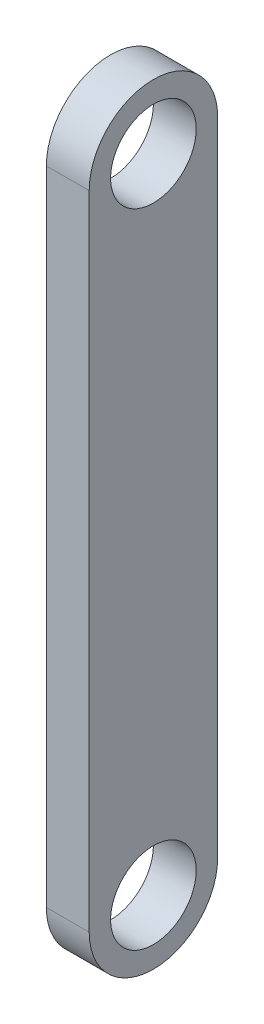
SolidWorks part; units mm, degrees
ref_plane "正面" through (0, 0, 0) normal (0, 0, 1) x (1, 0, 0)
ref_plane "平面" through (0, 0, 0) normal (0, 1, 0) x (1, 0, 0)
ref_plane "右側面" through (0, 0, 0) normal (1, 0, 0) x (0, 0, -1)
sketch "ｽｹｯﾁ1" plane through (0, 0, 0) normal (1, 0, 0) x (0, 0, -1)
  line L1 (22.914, 40.8023) -> (25.914, 40.8023)
  line L2 (25.914, 40.8023) -> (25.914, 10.8023)
  line L3 (25.914, 10.8023) -> (19.914, 10.8023)
  line L4 (19.914, 10.8023) -> (19.914, 40.8023)
  circle A0 centre (22.914, 40.8023) radius 2
  circle A1 centre (22.914, 10.8023) radius 2
  circle A2 centre (22.914, 40.8023) radius 3
  circle A3 centre (22.914, 10.8023) radius 3
extrude "ﾎﾞｽ - 押し出し1" add sketch "ｽｹｯﾁ1" along normal blind 2
